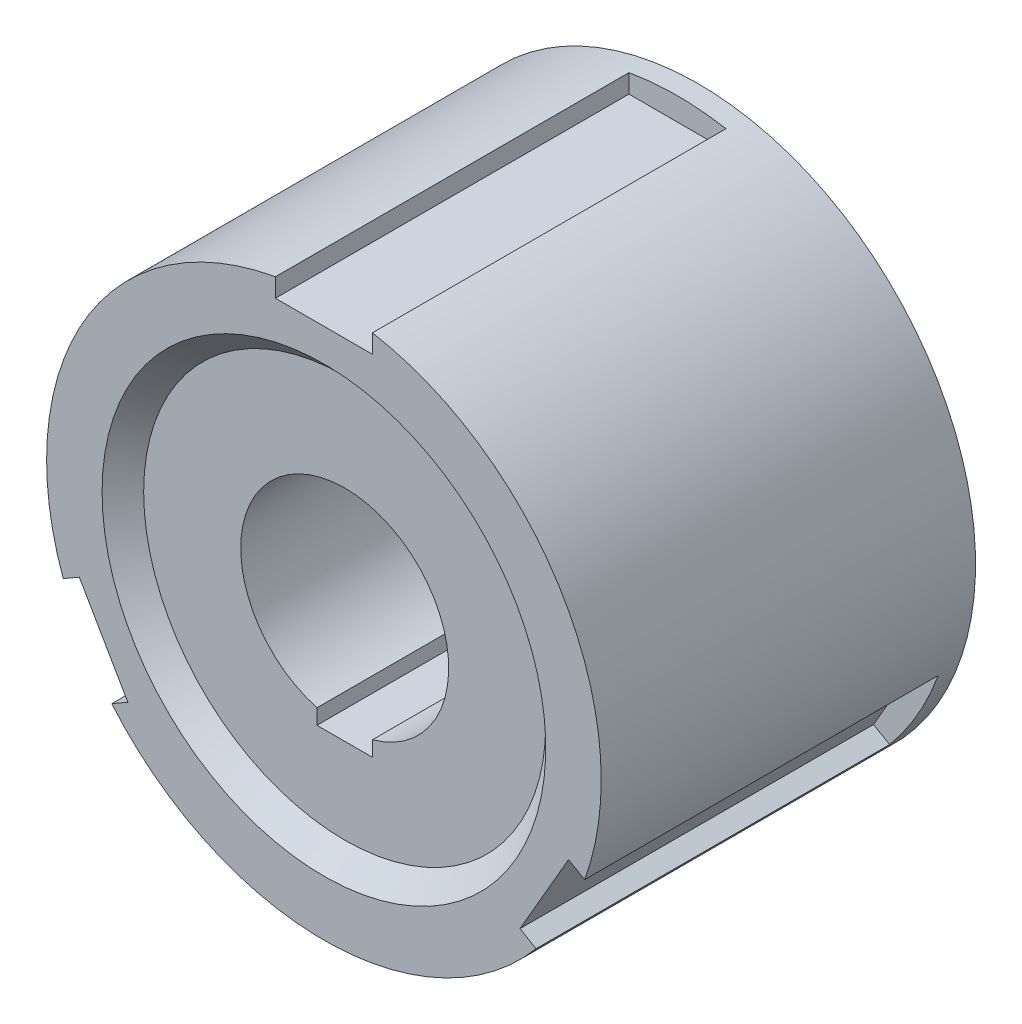
SolidWorks part; units mm, degrees
ref_plane "Plan de face" through (0, 0, 0) normal (0, 0, 1) x (1, 0, 0)
ref_plane "Plan de dessus" through (0, 0, 0) normal (0, 1, 0) x (1, 0, 0)
ref_plane "Plan de droite" through (0, 0, 0) normal (1, 0, 0) x (0, 0, -1)
sketch "Esquisse1" plane through (0, 0, 0) normal (0, 0, 1) x (1, 0, 0)
  circle A0 centre (0, 0) radius 40
  circle A1 centre (0, 0) radius 15
  circle A2 centre (0, 0) radius 33
  dimension "D1" = 80
  dimension "D2" = 30
  dimension "D3" = 66
extrude "Boss.-Extru.1" add sketch "Esquisse1" along normal blind 58 contours A2 A1 | A0 A2
sketch "Esquisse2" plane through (0, 0, 58) normal (0, 0, 1) x (1, 0, 0)
  line L0 (0, 0) -> (0, -33.0337) construction
  line L10 (-4, -13.35) -> (4, -13.35)
  line L11 (-4, -13.35) -> (-4, -16.65)
  line L12 (-4, -16.65) -> (4, -16.65)
  line L13 (4, -13.35) -> (4, -16.65)
  line L14 (-4, -13.35) -> (4, -16.65) construction
  line L15 (-4, -16.65) -> (4, -13.35) construction
  circle A3 centre (0, 0) radius 15
  point P2 (0, -15)
  point P8 (0, -16.65)
  dimension "D1" = 30
  dimension "D3" = 16.65
  dimension "D2" = 8
extrude "Enlèv. mat.-Extru.1" cut sketch "Esquisse2" against normal through all contours L11 L12 L13 L10
sketch "Esquisse3" plane through (0, 0, 58) normal (0, 0, 1) x (1, 0, 0)
  line L0 (0, 49.6887) -> (0, -54.9124) construction
  line L1 (-54.903, 31.6983) -> (54.903, -31.6983) construction
  line L2 (-7, 43.3006) -> (7, 43.3006)
  line L3 (-7, 43.3006) -> (-7, 36.6994)
  line L4 (-7, 36.6994) -> (7, 36.6994)
  line L5 (7, 43.3006) -> (7, 36.6994)
  line L6 (-7, 43.3006) -> (7, 36.6994) construction
  line L7 (-7, 36.6994) -> (7, 43.3006) construction
  line L8 (-69.5681, -40.1652) -> (69.5681, 40.1652) construction
  line L9 (28.2826, -24.4119) -> (40.9995, -15.5881) construction
  line L10 (33.9995, -27.7125) -> (35.2826, -12.2875) construction
  line L11 (40.9995, -15.5881) -> (35.2826, -12.2875)
  line L12 (28.2826, -24.4119) -> (35.2826, -12.2875)
  line L13 (33.9995, -27.7125) -> (28.2826, -24.4119)
  line L14 (33.9995, -27.7125) -> (40.9995, -15.5881)
  line L15 (-35.2826, -12.2875) -> (-33.9995, -27.7125) construction
  line L16 (-40.9995, -15.5881) -> (-28.2826, -24.4119) construction
  line L17 (-33.9995, -27.7125) -> (-28.2826, -24.4119)
  line L18 (-35.2826, -12.2875) -> (-28.2826, -24.4119)
  line L19 (-40.9995, -15.5881) -> (-35.2826, -12.2875)
  line L20 (-40.9995, -15.5881) -> (-33.9995, -27.7125)
  circle A0 centre (0, 0) radius 40
  point P5 (0, 40)
  point P18 (34.641, -20)
  point P23 (-34.641, -20)
  circle M6 centre (0, 0) radius 40
  dimension "D1" = 80
  dimension "D2" = 14
  dimension "D3" = 120
  dimension "D4" = 120
extrude "Enlèv. mat.-Extru.2" cut sketch "Esquisse3" against normal blind 51 contours L13 L14 L11 M6 | L13 L11 L12 M6 | L19 L20 L17 M6 | L19 L17 L18 M6 | L5 L3 L4 M6 | L5 L2 L3 M6
sketch "Esquisse4" plane through (0, 0, 0) normal (0, 0, -1) x (-1, 0, 0)
  circle A0 centre (0, 0) radius 33
  circle A1 centre (0, 0) radius 40
  dimension "D1" = 66
  dimension "D2" = 80
extrude "Enlèv. mat.-Extru.3" cut sketch "Esquisse4" against normal blind 4
sketch "Esquisse7" plane through (0, 0, 0) normal (1, 0, 0) x (0, 0, -1)
  line L0 (0, 0) -> (-107.9415, 0) construction
  line L1 (-58, 32) -> (-55, 29)
  line L2 (-58, 39.3827) -> (-58, -13.6292) construction
  line L3 (-55, 29) -> (-55, 0)
  line L5 (-58, 0) -> (-58, 32)
  line L6 (-58, 0) -> (-55, 0)
  dimension "D2" = 45
  dimension "D3" = 3
revolve "Enlèvement de matière-Révolution2" cut sketch "Esquisse7" angle 360 about L0
